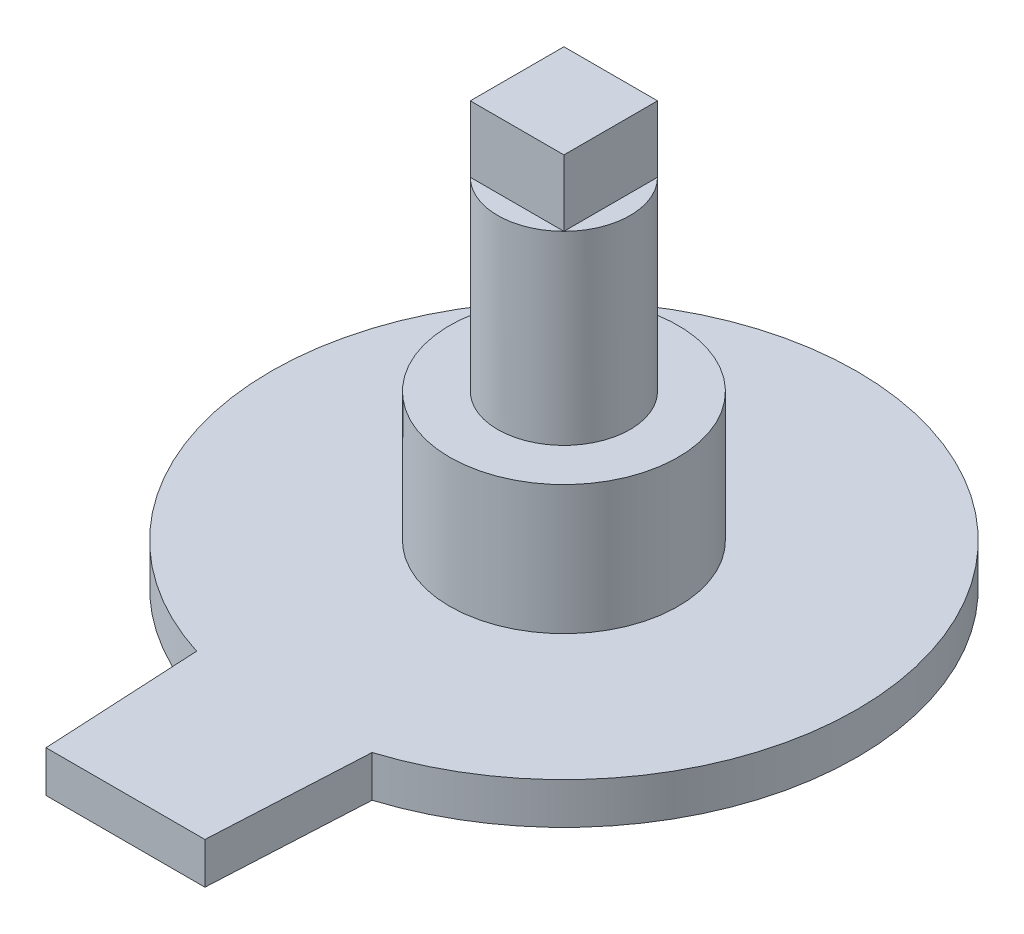
SolidWorks part; units mm, degrees
ref_plane "Front Plane" through (0, 0, 0) normal (0, 0, 1) x (1, 0, 0)
ref_plane "Top Plane" through (0, 0, 0) normal (0, 1, 0) x (1, 0, 0)
ref_plane "Right Plane" through (0, 0, 0) normal (1, 0, 0) x (0, 0, -1)
sketch "Sketch1" plane through (0, 0, 0) normal (0, 1, 0) x (1, 0, 0)
  circle A0 centre (0, 0) radius 8.85
  dimension "D1" = 17.7
extrude "Boss-Extrude1" add sketch "Sketch1" along normal blind 1.25
sketch "Sketch2" plane through (0, 1.25, 0) normal (0, 1, 0) x (1, 0, 0)
  circle A0 centre (0, 0) radius 3.45
  dimension "D1" = 6.9
extrude "Boss-Extrude2" add sketch "Sketch2" along normal blind 3.9
sketch "Sketch3" plane through (0, 5.15, 0) normal (0, 1, 0) x (1, 0, 0)
  circle A0 centre (0, 0) radius 2
  dimension "D1" = 4
extrude "Boss-Extrude3" add sketch "Sketch3" along normal blind 5.6
sketch "Sketch4" plane through (0, 10.75, 0) normal (0, 1, 0) x (1, 0, 0)
  line L1 (-1.4142, -1.4142) -> (1.4142, -1.4142)
  line L2 (-1.4142, -1.4142) -> (-1.4142, 1.4142)
  line L3 (-1.4142, 1.4142) -> (1.4142, 1.4142)
  line L4 (1.4142, -1.4142) -> (1.4142, 1.4142)
  line L5 (-1.4142, -1.4142) -> (1.4142, 1.4142) construction
  line L6 (-1.4142, 1.4142) -> (1.4142, -1.4142) construction
  circle A0 centre (0, 0) radius 2 construction
  point P0 (0, 0)
  point P8 (0, 1.4142)
extrude "Boss-Extrude4" add sketch "Sketch4" along normal blind 2
sketch "Sketch5" plane through (0, 0, 0) normal (0, -1, 0) x (1, 0, 0)
  line L0 (0, 0) -> (0, 13.2439)
  line L1 (0, 13.2439) -> (2.4, 13.2439)
  line L2 (2.4, 13.2439) -> (2.65, 8.4439)
  line L3 (2.65, 8.4439) -> (-2.65, 8.4439)
  line L4 (-2.65, 8.4439) -> (-2.4, 13.2439)
  line L5 (-2.4, 13.2439) -> (0, 13.2439)
  circle A0 centre (0, 0) radius 8.85 construction
  point P3 (-1.2727, 11.68)
  circle M6 centre (0, 0) radius 8.85
  dimension "D1" = 5.3
  dimension "D2" = 4.8
  dimension "D3" = 4.8
extrude "Boss-Extrude5" add sketch "Sketch5" against normal blind 1.25 contours L5 L4 L0 M6 | L2 L1 L0 M6
